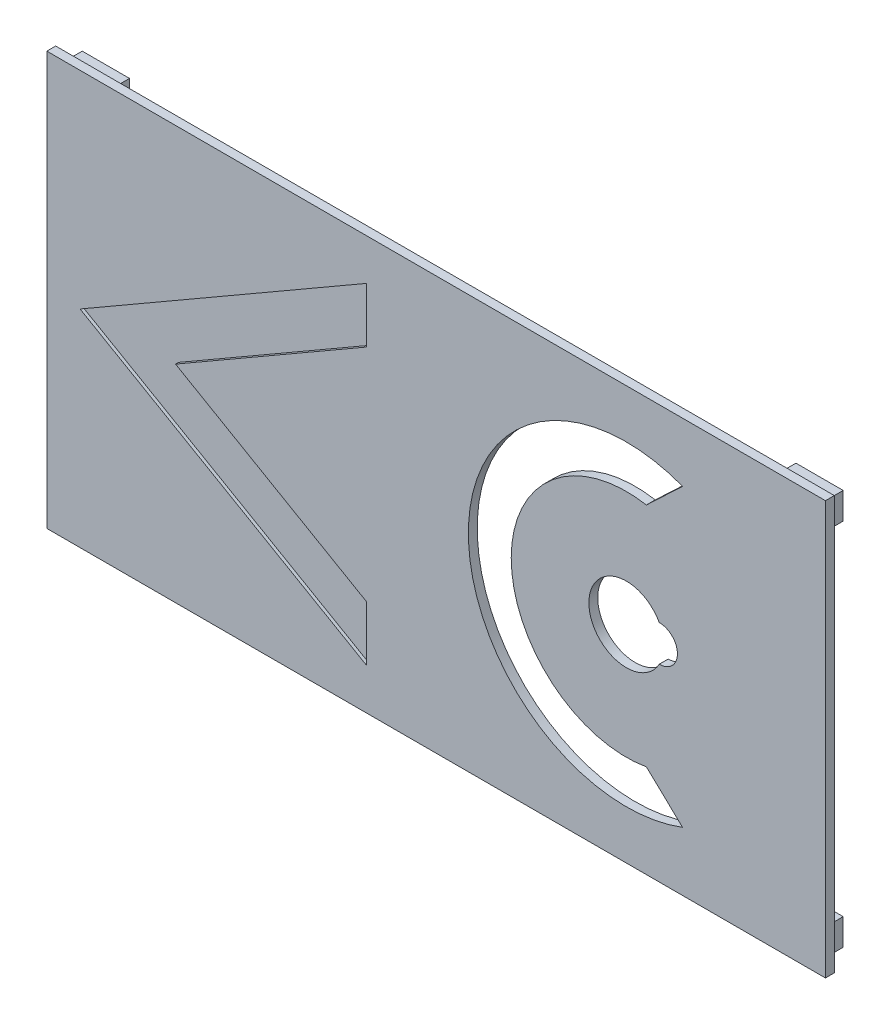
SolidWorks part; units mm, degrees
ref_plane "Front Plane" through (0, 0, 0) normal (0, 0, 1) x (1, 0, 0)
ref_plane "Top Plane" through (0, 0, 0) normal (0, 1, 0) x (1, 0, 0)
ref_plane "Right Plane" through (0, 0, 0) normal (1, 0, 0) x (0, 0, -1)
sketch "Sketch1" plane through (0, 0, 0) normal (0, 0, 1) x (1, 0, 0)
  line L0 (121.1, -9.75) -> (-10.75, -9.75)
  line L1 (119.6, -8.25) -> (-9.25, -8.25)
  line L2 (119.6, -8.25) -> (119.6, 58.75)
  line L3 (119.6, 58.75) -> (-9.25, 58.75)
  line L4 (-9.25, -8.25) -> (-9.25, 58.75)
  line L5 (-10.75, -9.75) -> (-10.75, 60.25)
  line L6 (121.1, 60.25) -> (-10.75, 60.25)
  line L7 (121.1, -9.75) -> (121.1, 60.25)
  dimension "D1" = 1.5
extrude "Boss-Extrude1" add sketch "Sketch1" along normal blind 1.5 contours L7 L6 L5 L0
sketch "Sketch2" plane through (0, 0, 1.5) normal (0, 0, 1) x (1, 0, 0)
  line L5 (92.9571, 22.2) -> (92.9875, 22.2)
  line L6 (92.9875, 28.3) -> (92.9571, 28.3)
  line L7 (92.9571, 22.2) -> (92.9875, 22.2)
  line L8 (92.9875, 28.3) -> (92.9571, 28.3)
  arc A10 (92.9875, 22.2) -> (92.9875, 28.3) centre (92.9875, 25.25) ccw
  arc A11 (92.9571, 28.3) -> (92.9571, 22.2) centre (87.3875, 25.25) ccw
  arc A12 (92.9875, 22.2) -> (92.9875, 28.3) centre (92.9875, 25.25) ccw
  arc A13 (92.9571, 28.3) -> (92.9571, 22.2) centre (87.3875, 25.25) ccw
  dimension "D1" = 0.25
extrude "Cut-Extrude1" cut sketch "Sketch2" against normal up to next
ref_plane "Plane2" through (0, 25.25, 0) normal (0, 1, 0) x (1, 0, 0)
ref_plane "Plane1" through (55.175, 0, 0) normal (1, 0, 0) x (0, 0, -1)
sketch "Sketch3" plane through (121.1, 0, 0) normal (1, 0, 0) x (0, 0, -1)
  line L0 (0, -9.75) -> (0, 60.25) construction
  line L1 (-1.5, 60.25) -> (6, 60.25)
  line L2 (-1.5, 60.25) -> (-1.5, 61.75)
  line L3 (-1.5, 61.75) -> (6, 61.75)
  line L4 (6, 60.25) -> (6, 61.75)
  line L5 (6, 60.25) -> (4.5, 58.75)
  line L7 (4.5, 58.75) -> (4.5, 60.25)
  dimension "D1" = 1.5
  dimension "D2" = 6
  dimension "D3" = 45
sketch "Sketch4" plane through (0, 0, 0) normal (0, 0, -1) x (-1, 0, 0)
  line L0 (-118.1, 57.25) -> (-118.1, 55.75)
  line L1 (-119.6, 58.75) -> (-111.6, 58.75)
  line L2 (-119.6, 58.75) -> (-119.6, 54.25)
  line L3 (-119.6, 54.25) -> (-111.6, 54.25)
  line L4 (-111.6, 58.75) -> (-111.6, 54.25)
  line L5 (-119.6, 58.75) -> (-119.6, 60.25) construction
  line L6 (-118.1, 55.75) -> (-113.1, 55.75)
  line L7 (-121.1, 60.25) -> (10.75, 60.25) construction
  line L8 (-113.1, 57.25) -> (-113.1, 55.75)
  line L9 (-118.1, 57.25) -> (-113.1, 57.25)
  line L10 (-119.6, 58.75) -> (-121.1, 58.75) construction
  line L11 (-121.1, -9.75) -> (-121.1, 60.25) construction
  dimension "D1" = 1.5
  dimension "D2" = 5
  dimension "D3" = 1.5
extrude "Boss-Extrude2" add sketch "Sketch4" along normal blind 3
mirror "Mirror1" about plane through (0, 25.25, 0) normal (0, 1, 0) of "Boss-Extrude2"
mirror "Mirror2" about plane through (55.175, 0, 0) normal (1, 0, 0) of "Mirror1", "Boss-Extrude2"
sketch "Sketch5" plane through (0, 0, 1.5) normal (0, 0, 1) x (1, 0, 0)
  line L0 (62.3875, 28.95) -> (62.3875, 21.55) construction
  line L1 (62.3875, 28.95) -> (62.3875, 21.55) construction
  line L2 (60.8875, 28.95) -> (60.8875, 21.55) construction
  line L3 (60.8875, 28.95) -> (60.8875, 21.55) construction
  line L4 (60.8875, 28.95) -> (62.3875, 28.95) construction
  line L5 (60.8875, 28.95) -> (62.3875, 28.95) construction
  line L6 (60.8875, 21.55) -> (62.3875, 21.55) construction
  line L7 (60.8875, 21.55) -> (62.3875, 21.55) construction
  line L8 (67.8875, 21.55) -> (66.3875, 21.55) construction
  line L9 (67.8875, 28.95) -> (66.3875, 28.95) construction
  line L10 (67.8875, 26.1038) -> (67.8875, 24.3962) construction
  line L11 (90.7742, 6.0464) -> (96.9081, 0.244)
  line L12 (60.8875, 21.55) -> (67.8875, 21.55) construction
  line L13 (60.8875, 21.55) -> (60.8875, 28.95) construction
  line L14 (60.8875, 28.95) -> (67.8875, 28.95) construction
  line L15 (67.8875, 21.55) -> (67.8875, 28.95) construction
  line L16 (83.6875, 51.75) -> (91.0875, 51.75) construction
  line L17 (83.6875, 51.75) -> (83.6875, 44.75) construction
  line L18 (83.6875, 44.75) -> (91.0875, 44.75) construction
  line L19 (91.0875, 51.75) -> (91.0875, 44.75) construction
  line L20 (67.8875, 21.55) -> (70.3875, 21.55)
  line L21 (70.3875, 21.55) -> (70.3875, 28.95)
  line L22 (70.3875, 28.95) -> (67.8875, 28.95)
  line L23 (67.8875, 28.95) -> (67.8875, 26.1038)
  line L24 (67.8875, 26.1038) -> (66.3875, 26.1038)
  line L25 (66.3875, 26.1038) -> (66.3875, 28.95)
  line L26 (66.3875, 28.95) -> (63.8875, 28.95)
  line L27 (63.8875, 28.95) -> (63.8875, 21.55)
  line L28 (63.8875, 21.55) -> (66.3875, 21.55)
  line L29 (66.3875, 21.55) -> (66.3875, 24.3962)
  line L30 (66.3875, 24.3962) -> (67.8875, 24.3962)
  line L31 (67.8875, 24.3962) -> (67.8875, 21.55)
  line L32 (83.6875, 51.75) -> (91.0875, 44.75) construction
  line L33 (83.6875, 44.75) -> (91.0875, 51.75) construction
  line L34 (83.6875, 5.75) -> (91.0875, 5.75) construction
  line L35 (67.8875, 28.95) -> (67.8875, 26.1038) construction
  line L36 (67.8875, 26.1038) -> (66.3875, 26.1038) construction
  line L37 (66.3875, 26.1038) -> (66.3875, 28.95) construction
  line L38 (83.6875, 5.75) -> (83.6875, -1.25) construction
  line L39 (83.6875, -1.25) -> (91.0875, -1.25) construction
  line L40 (91.0875, 5.75) -> (91.0875, -1.25) construction
  line L41 (66.3875, 21.55) -> (66.3875, 24.3962) construction
  line L42 (66.3875, 24.3962) -> (67.8875, 24.3962) construction
  line L43 (67.8875, 24.3962) -> (67.8875, 21.55) construction
  line L44 (83.6875, 5.75) -> (91.0875, -1.25) construction
  line L45 (83.6875, -1.25) -> (91.0875, 5.75) construction
  line L46 (90.7742, 44.4536) -> (96.9081, 50.256)
  arc A0 (96.9081, 50.256) -> (96.9081, 0.244) centre (87.3875, 25.25) ccw
  arc A1 (90.7742, 44.4536) -> (90.7742, 6.0464) centre (87.3875, 25.25) ccw
  point P19 (67.8875, 25.25)
  point P20 (87.3875, 48.25)
  point P25 (87.3875, 2.25)
  point P26 (87.3875, 44.75)
  point P32 (87.3875, 5.75)
  dimension "D1" = 0
extrude "Cut-Extrude2" cut sketch "Sketch5" against normal up to next
sketch "Sketch6" plane through (0, 0, 1.5) normal (0, 0, 1) x (1, 0, 0)
  line L0 (87.3875, 25.25) -> (43.3775, 25.25) construction
  line L1 (56.3875, -2.75) -> (43.3775, -2.75) construction
  line L2 (-5.1199, 25.25) -> (43.3775, -2.75)
  line L3 (43.3775, -2.75) -> (43.3775, 6.5833)
  line L4 (43.3775, 53.25) -> (-5.1199, 25.25)
  line L5 (43.3775, 6.5833) -> (43.3775, -2.75) construction
  line L6 (11.0459, 25.25) -> (43.3775, 6.5833)
  line L7 (43.3775, 25.25) -> (-5.1199, 25.25) construction
  line L8 (43.3775, 43.9167) -> (11.0459, 25.25)
  line L9 (43.3775, 43.9167) -> (43.3775, 53.25)
  line L10 (43.3775, 43.9167) -> (43.3775, 6.5833) construction
  line L11 (43.3775, 6.5833) -> (43.3775, -2.75) construction
  line L13 (43.3775, 25.25) -> (43.3775, 43.9167) [skipped]
  circle A0 centre (27.2117, 25.25) radius 16.1658 construction
  circle A1 centre (32.6003, 25.25) radius 10.7772 construction
  dimension "D1" = 44.01
extrude "Cut-Extrude3" cut sketch "Sketch6" against normal blind 0.5
equation "\"D1@Boss-Extrude2\"=1.50mm+.25"
